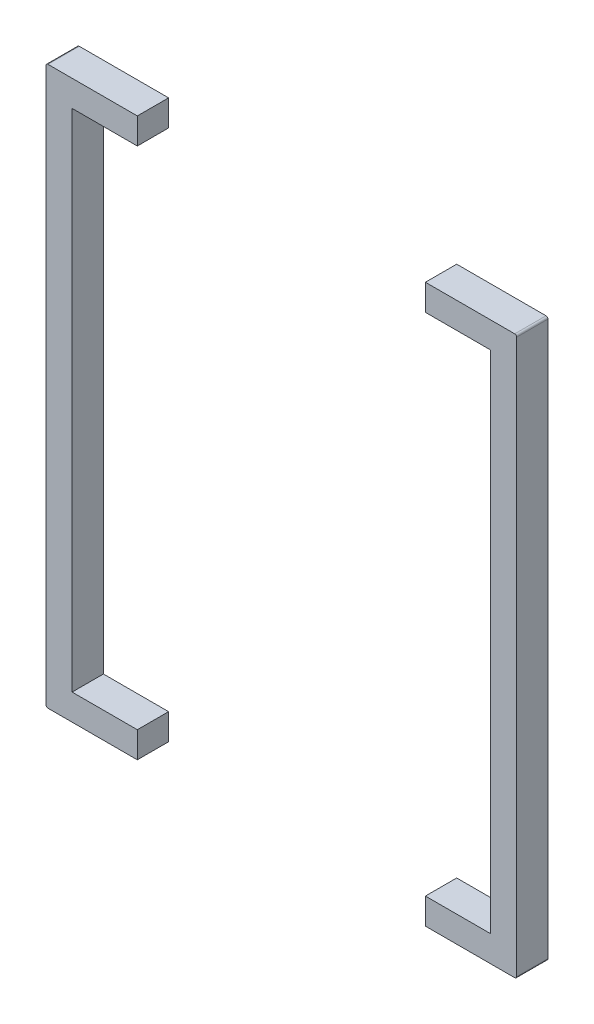
SolidWorks part; units mm, degrees
material "Melamine resin"
ref_plane "Plano frontal" through (0, 0, 0) normal (0, 0, 1) x (1, 0, 0)
ref_plane "Plano superior" through (0, 0, 0) normal (0, 1, 0) x (1, 0, 0)
ref_plane "Plano direito" through (0, 0, 0) normal (1, 0, 0) x (0, 0, -1)
sketch "Esboço1" plane through (0, 0, 0) normal (0, 0, 1) x (1, 0, 0)
  line L1 (-76.152, 222.0831) -> (104.318, 222.0831)
  line L2 (-76.152, 222.0831) -> (-76.152, 8.2431)
  line L3 (-76.152, 8.2431) -> (104.318, 8.2431)
  line L4 (104.318, 222.0831) -> (104.318, 8.2431)
  dimension "D1" = 180.47
  dimension "D2" = 213.84
extrude "Ressalto-extrusão1" add sketch "Esboço1" along normal blind 12
fillet "Filete2" radius 0.7366 1 edges at (104.318, 222.0831, 6)
fillet "Filete3" radius 0.7366 1 edges at (104.318, 8.2431, 6)
fillet "Filete4" radius 0.7366 1 edges at (-76.152, 8.2431, 6)
fillet "Filete5" radius 0.7366 1 edges at (-76.152, 222.0831, 6)
sketch "Esboço2" plane through (0, 0, 12) normal (0, 0, 1) x (1, 0, 0)
  line L0 (69.318, 222.0831) -> (103.5846, 222.0831) construction
  line L1 (-66.152, 212.0831) -> (94.318, 212.0831)
  line L2 (-66.152, 212.0831) -> (-66.152, 18.2431)
  line L3 (-66.152, 18.2431) -> (94.318, 18.2431)
  line L4 (94.318, 212.0831) -> (94.318, 18.2431)
  line L5 (104.318, 8.9797) -> (104.318, 221.3465) construction
  line L6 (-75.4154, 8.2431) -> (103.5814, 8.2431) construction
  line L7 (-76.152, 221.3465) -> (-76.152, 8.9797) construction
  dimension "D1" = 10
  dimension "D2" = 10
  dimension "D3" = 10
  dimension "D4" = 10
extrude "Corte-extrusão1" cut sketch "Esboço2" against normal up to next
sketch "Esboço5" plane through (0, 222.0831, 0) normal (0, 1, 0) x (-1, 0, 0)
  line L0 (-103.5814, 0) -> (75.4154, 0) construction
  line L1 (-69.318, 0) -> (41.152, 0)
  line L2 (-69.318, 0) -> (-69.318, 12)
  line L3 (-69.318, 12) -> (41.152, 12)
  line L4 (41.152, 0) -> (41.152, 12)
  line L5 (-103.5814, 12) -> (75.4154, 12) construction
  line L6 (76.152, 12) -> (76.152, 0) construction
  line L7 (-104.318, 0) -> (-104.318, 12) construction
  dimension "D1" = 35
  dimension "D2" = 35
extrude "Corte-extrusão2" cut sketch "Esboço5" against normal up to next
sketch "Esboço6" plane through (0, 8.2431, 0) normal (0, -1, 0) x (1, 0, 0)
  line L0 (-75.4154, 12) -> (103.5814, 12) construction
  line L1 (69.318, 12) -> (-41.152, 12)
  line L2 (69.318, 12) -> (69.318, 0)
  line L3 (69.318, 0) -> (-41.152, 0)
  line L4 (-41.152, 12) -> (-41.152, 0)
  line L5 (-75.4154, 0) -> (103.5814, 0) construction
  line L6 (-76.152, 0) -> (-76.152, 12) construction
  line L7 (104.318, 12) -> (104.318, 0) construction
  dimension "D1" = 35
  dimension "D2" = 35
extrude "Corte-extrusão3" cut sketch "Esboço6" against normal up to next
